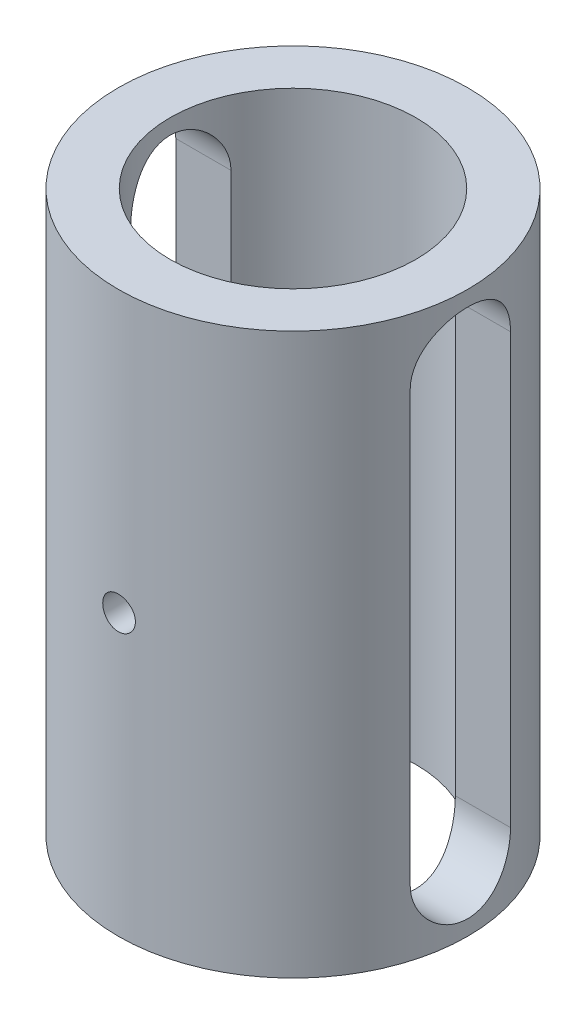
SolidWorks part; units mm, degrees
ref_plane "Front Plane" through (0, 0, 0) normal (0, 0, 1) x (1, 0, 0)
ref_plane "Top Plane" through (0, 0, 0) normal (0, 1, 0) x (1, 0, 0)
ref_plane "Right Plane" through (0, 0, 0) normal (1, 0, 0) x (0, 0, -1)
sketch "Sketch1" plane through (0, 0, 0) normal (0, 1, 0) x (1, 0, 0)
  circle A0 centre (0, 0) radius 8.0883
  circle A1 centre (0, 0) radius 11.5
  dimension "D1" = 16.1766
  dimension "D2" = 23
extrude "Boss-Extrude1" add sketch "Sketch1" along normal blind 36.88
ref_plane "Plane1" through (-11.5, 0, 0) normal (-1, 0, 0) x (0, 0, 1)
sketch "Sketch2" plane through (-11.5, 0, 0) normal (-1, 0, 0) x (0, 0, 1)
  line L0 (0, 32.5733) -> (0, 4.3067) construction
  line L1 (3.302, 32.5733) -> (3.302, 4.3067)
  line L2 (-3.302, 32.5733) -> (-3.302, 4.3067)
  line L3 (0, 32.5733) -> (0, 36.88) construction
  line L4 (8.0883, 36.88) -> (-8.0883, 36.88) construction
  line L5 (0, 4.3067) -> (0, 0) construction
  arc A0 (3.302, 32.5733) -> (-3.302, 32.5733) centre (0, 32.5733) ccw
  arc A1 (-3.302, 4.3067) -> (3.302, 4.3067) centre (0, 4.3067) ccw
  point P3 (0, 18.44)
  dimension "D1" = 3.302
extrude "Cut-Extrude1" cut sketch "Sketch2" against normal blind 55.88
sketch "Sketch3" plane through (0, 0, 0) normal (0, 0, 1) x (1, 0, 0)
  line L0 (0, 36.88) -> (0, 18.44) construction
  line L1 (11.5, 36.88) -> (-11.5, 36.88) construction
  circle A0 centre (0, 18.44) radius 1.0754
extrude "Cut-Extrude2" cut sketch "Sketch3" along normal through all
